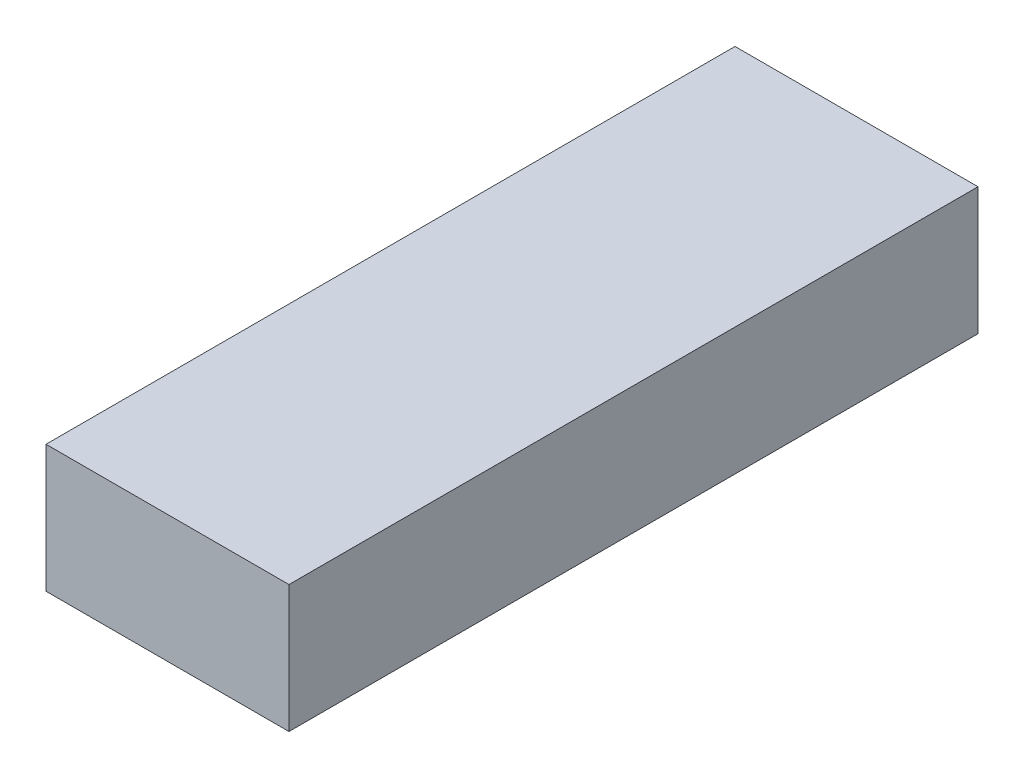
SolidWorks part; units mm, degrees
ref_plane "Front Plane" through (0, 0, 0) normal (0, 0, 1) x (1, 0, 0)
ref_plane "Top Plane" through (0, 0, 0) normal (0, 1, 0) x (1, 0, 0)
ref_plane "Right Plane" through (0, 0, 0) normal (1, 0, 0) x (0, 0, -1)
sketch "Sketch1" plane through (0, 0, 0) normal (0, 1, 0) x (1, 0, 0)
  line L1 (-292, -828) -> (292, -828)
  line L2 (-292, -828) -> (-292, 828)
  line L3 (-292, 828) -> (292, 828)
  line L4 (292, -828) -> (292, 828)
  line L5 (-292, -828) -> (292, 828) construction
  line L6 (-292, 828) -> (292, -828) construction
  point P0 (0, 0)
  dimension "D1" = 1656
  dimension "D2" = 584
extrude "Boss-Extrude1" add sketch "Sketch1" along normal blind 306
